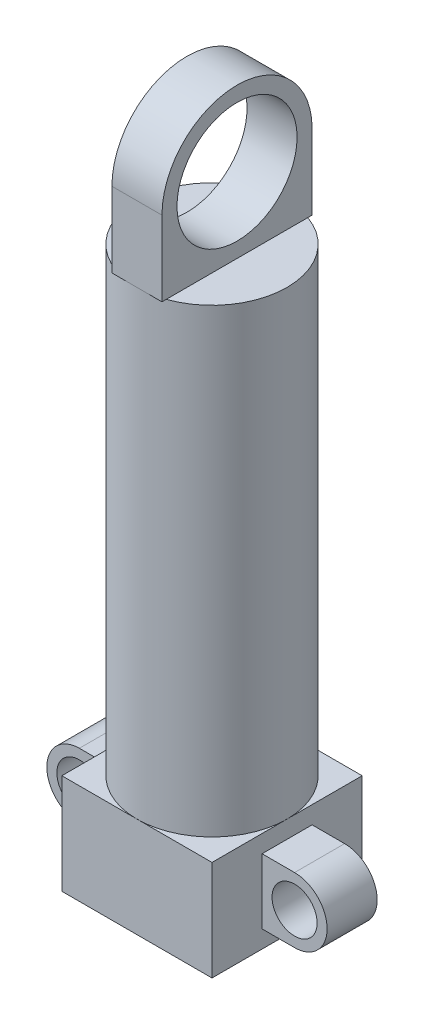
SolidWorks part; units mm, degrees
ref_plane "Front Plane" through (0, 0, 0) normal (0, 0, 1) x (1, 0, 0)
ref_plane "Top Plane" through (0, 0, 0) normal (0, 1, 0) x (1, 0, 0)
ref_plane "Right Plane" through (0, 0, 0) normal (1, 0, 0) x (0, 0, -1)
sketch "Sketch1" plane through (0, 0, 0) normal (0, 1, 0) x (1, 0, 0)
  circle A0 centre (0, 0) radius 7.5
extrude "Boss-Extrude1" add sketch "Sketch1" along normal blind 46
sketch "Sketch2" plane through (0, 0, 0) normal (0, -1, 0) x (1, 0, 0)
  line L0 (0, -7.5) -> (0, 7.5)
  line L5 (0, 7.5) -> (7.5, 7.5)
  line L6 (7.5, 7.5) -> (7.5, -7.5)
  line L7 (7.5, -7.5) -> (-7.5, -7.5)
  line L8 (-7.5, -7.5) -> (-7.5, 7.5)
  line L9 (-7.5, 7.5) -> (0, 7.5)
  circle A1 centre (0, 0) radius 7.5 construction
  circle M5 centre (0, 0) radius 7.5
extrude "Boss-Extrude2" add sketch "Sketch2" along normal blind 10 contours L0 M5 | L0 M5 | L7 L6 M5
sketch "Sketch3" plane through (-7.5, 0, 0) normal (-1, 0, 0) x (0, 0, 1)
  line L0 (0, -10) -> (0, -5)
  line L1 (-7.5, -10) -> (7.5, -10) construction
  circle A1 centre (0, -5) radius 2.5
  dimension "D1" = 5
  dimension "D2" = 5
sketch "Sketch4" plane through (0, 46, 0) normal (0, 1, 0) x (1, 0, 0)
  line L0 (0, 7.5) -> (7.5, 7.5)
  line L1 (7.5, 7.5) -> (7.5, -7.5)
  line L2 (7.5, -7.5) -> (-7.5, -7.5)
  line L3 (-7.5, -7.5) -> (-7.5, 7.5)
  line L4 (-7.5, 7.5) -> (0, 7.5)
  circle A0 centre (0, 0) radius 7.5 construction
extrude "Boss-Extrude3" add sketch "Sketch4" along normal blind 15
sketch "Sketch5" plane through (-7.5, 0, 0) normal (-1, 0, 0) x (0, 0, 1)
  line L0 (0, 61) -> (0, 53.5)
  line L1 (-7.5, 61) -> (7.5, 61) construction
  line L2 (0, 61) -> (7.5, 61)
  line L3 (7.5, 61) -> (7.5, 46)
  line L4 (7.5, 46) -> (-7.5, 46)
  line L5 (-7.5, 46) -> (-7.5, 61)
  line L6 (-7.5, 61) -> (7.5, 61)
  circle A0 centre (0, 53.5) radius 7.5
  line M6 (7.5, 61) -> (-7.5, 61)
  line M7 (-7.5, 61) -> (-7.5, 46)
  dimension "D1" = 7.5
extrude "Cut-Extrude4" cut sketch "Sketch5" against normal through all contours A0 M6 M7 | A0 L3 M6
sketch "Sketch6" plane through (-7.5, 0, 0) normal (-1, 0, 0) x (0, 0, 1)
  line L0 (0, 61) -> (0, 53.5)
  arc A0 (7.5, 53.5) -> (-7.5, 53.5) centre (0, 53.5) ccw construction
  circle A1 centre (0, 53.5) radius 6
extrude "Cut-Extrude5" cut sketch "Sketch6" against normal through all
sketch "Sketch7" plane through (-7.5, 0, 0) normal (-1, 0, 0) x (0, 0, 1)
  line L0 (-7.5, 53.5) -> (-7.5, 46)
  line L1 (-7.5, 46) -> (0, 46) construction
  line L2 (-7.5, 53.5) -> (-7.5, 46) construction
  line L3 (-7.5, 46) -> (7.5, 46)
  line L4 (7.5, 46) -> (7.5, 53.5)
  circle A0 centre (0, 53.5) radius 7.5
  circle M1 centre (0, 53.5) radius 6
  line M2 (7.5, 46) -> (7.5, 53.5)
  arc M3 (7.5, 53.5) -> (-7.5, 53.5) centre (0, 53.5) ccw
  line M4 (-7.5, 53.5) -> (-7.5, 46)
  line M5 (-7.5, 46) -> (0, 46)
  line M6 (0, 46) -> (7.5, 46)
extrude "Cut-Extrude6" cut sketch "Sketch7" against normal blind 5 from offset 0 contours A0 M4 M5 | A0 M6 M2 | A0 M3 M1 | M1
sketch "Sketch10" plane through (7.5, 0, 0) normal (1, 0, 0) x (0, 0, -1)
  line L0 (6, 53.5) -> (7.5, 53.5)
  line L1 (7.5, 53.5) -> (7.5, 46)
  line L2 (7.5, 46) -> (-7.5, 46)
  line L3 (-7.5, 46) -> (-7.5, 53.5)
  line L4 (-7.5, 53.5) -> (-6, 53.5)
  circle A0 centre (0, 53.5) radius 6 construction
  circle A1 centre (0, 53.5) radius 6
  circle M1 centre (0, 53.5) radius 6
  arc M2 (7.5, 53.5) -> (-7.5, 53.5) centre (0, 53.5) ccw
  line M3 (-7.5, 53.5) -> (-7.5, 46)
  line M4 (-7.5, 46) -> (0, 46)
  line M5 (0, 46) -> (7.5, 46)
  line M6 (7.5, 46) -> (7.5, 53.5)
extrude "Cut-Extrude7" cut sketch "Sketch10" against normal blind 5 contours L4 L0 M3 M4 M5 M6 M1 | L4 L0 M2 M1
ref_plane "Plane1" through (0, 0, 0) normal (0, 0, -1) x (-1, 0, 0)
sketch "Sketch11" plane through (0, 0, 0) normal (0, 0, -1) x (-1, 0, 0)
  line L0 (7.5, -10) -> (7.5, -5)
  line L1 (7.5, -7.5) -> (7.5, -2.5) construction
  line L9 (10.75, -8.25) -> (7.5, -8.25)
  line L11 (7.5, -8.25) -> (7.5, -1.75)
  line L13 (7.5, -10) -> (7.5, 0) construction
  line L14 (7.5, -1.75) -> (10.75, -1.75)
  circle A0 centre (10.75, -5) radius 3.25
  circle A1 centre (10.75, -5) radius 2.25
extrude "Boss-Extrude4" add sketch "Sketch11" along normal mid plane 5 contours A0 L14 L11 | A0 L0 L9 | A0 A1
sketch "Sketch12" plane through (0, 0, 0) normal (0, 0, -1) x (-1, 0, 0)
  line L0 (10.75, -1.75) -> (-7.5, -1.75)
  line L1 (-7.5, -10) -> (-7.5, 0) construction
  line L2 (-7.5, -1.75) -> (-10.75, -1.75)
  line L3 (-10.75, -1.75) -> (-10.75, -8.25)
  line L4 (-10.75, -8.25) -> (-7.5, -8.25)
  line L5 (-10.75, -1.75) -> (-10.75, -2.75)
  line L6 (-10.75, -8.25) -> (-10.75, -7.25)
  line L7 (-7.5, -5) -> (-10.75, -5)
  line L8 (-7.5, -1.75) -> (-7.5, -8.25)
  circle A0 centre (-10.75, -5) radius 2.25
  circle A1 centre (-10.75, -5) radius 3.25
extrude "Boss-Extrude5" add sketch "Sketch12" along normal mid plane 5 contours A1 L4 L8 | A1 L8 L2 | L3 A1 L7 A0 | L7 A1 L3 A0 | L3 A1 A0
